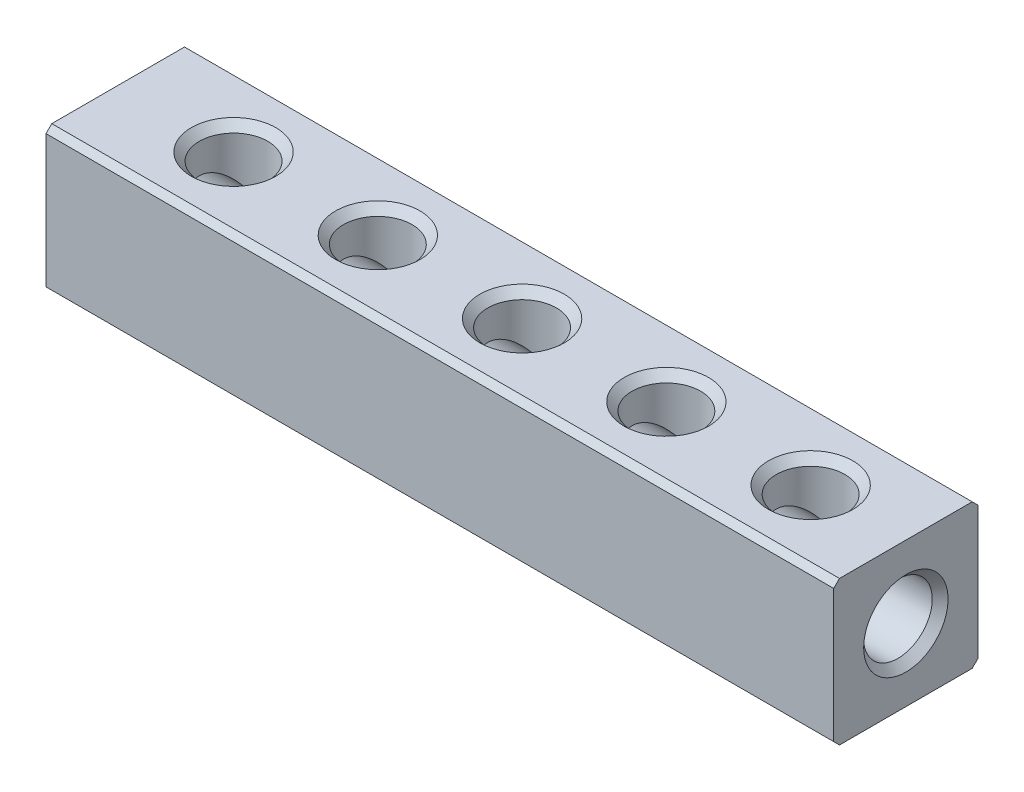
SolidWorks part; units mm, degrees
ref_plane "Front Plane" through (0, 0, 0) normal (0, 0, 1) x (1, 0, 0)
ref_plane "Top Plane" through (0, 0, 0) normal (0, 1, 0) x (1, 0, 0)
ref_plane "Right Plane" through (0, 0, 0) normal (1, 0, 0) x (0, 0, -1)
sketch "Sketch1" plane through (0, 0, 0) normal (0, 0, 1) x (1, 0, 0)
  line L1 (0, 0) -> (136.5, 0)
  line L2 (0, 0) -> (0, -25)
  line L3 (0, -25) -> (136.5, -25)
  line L4 (136.5, 0) -> (136.5, -25)
  dimension "D1" = 136.5
  dimension "D2" = 25
extrude "Boss-Extrude1" add sketch "Sketch1" along normal blind 25
sketch "Sketch4" plane through (0, 0, 0) normal (-1, 0, 0) x (0, 0, 1)
  line L0 (25, -25) -> (0, -25) construction
  line L1 (25, 0) -> (25, -25) construction
  circle A0 centre (12.5, -12.5) radius 6.55
  point P0 (12.5, -12.5)
  dimension "D1" = 13.1
  dimension "D2" = 12.5
  dimension "D3" = 12.5
sketch "Sketch5" plane through (0, -25, 0) normal (0, -1, 0) x (1, 0, 0)
  line L0 (0, 0) -> (136.5, 0) construction
  line L1 (0, 25) -> (0, 0) construction
  circle A0 centre (68.25, 12.5) radius 6.55
  dimension "D1" = 13.1
  dimension "D2" = 12.5
  dimension "D3" = 68.25
sketch "Sketch6" plane through (0, 0, 0) normal (0, 1, 0) x (1, 0, 0)
  line L0 (0, -25) -> (0, 0) construction
  line L1 (136.5, 0) -> (0, 0) construction
  circle A0 centre (20, -12.5) radius 6.55
  dimension "D1" = 13.1
  dimension "D2" = 20
  dimension "D3" = 12.5
hole_wizard "1/4-18 NPSM Tapped Hole2" positions "Sketch9" profile "Sketch10" tap size "1/4-18 NPSM" standard "ANSI Inch" end condition through all
sketch "Sketch9" plane through (0, 0, 0) normal (-1, 0, 0) x (0, 0, 1)
  point P0 (12.5, -12.5)
sketch "Sketch10" plane through (0, -12.5, 12.5) normal (0, 1, 0) x (0, 0, 1)
  line L0 (0, 0) -> (0, 136.5)
  line L1 (0, 136.5) -> (7.3152, 136.5)
  line L2 (5.9436, 135.1284) -> (5.9436, 1.3716)
  line L3 (5.9436, 1.3716) -> (7.3152, 0)
  line L5 (7.3152, 0) -> (0, 0)
  line L6 (-5.9436, 1.3716) -> (-7.3152, 0) construction
  line L7 (7.3152, 136.5) -> (5.9436, 135.1284)
  line L8 (-7.3152, 136.5) -> (-5.9436, 135.1284) construction
  line L11 (0, -6.35) -> (0, 107.95) construction
  dimension "Thru Tap Drill Dia." = 11.8872
  dimension "Thru Tap Drill Depth" = 136.5
  dimension "Near C'Sink Dia." = 14.6304
  dimension "Near C'Sink Angle" = 90
  dimension "Far C'Sink Dia." = 14.6304
  dimension "Far C'Sink Angle" = 90
cosmetic thread "Hole Thread2" parameters "D2"=13.3604
hole_wizard "1/4-18 NPSM Tapped Hole3" positions "Sketch22" profile "Sketch23" tap size "1/4-18 NPSM" standard "ANSI Inch"
sketch "Sketch22" plane through (0, -25, 0) normal (0, -1, 0) x (-1, 0, 0)
  point P0 (-68.25, -12.5)
sketch "Sketch23" plane through (68.25, -25, 12.5) normal (1, 0, 0) x (0, 0, -1)
  line L0 (0, 0) -> (0, 16.0703)
  line L1 (0, 16.0703) -> (5.9436, 12.499)
  line L2 (5.9436, 12.499) -> (5.9436, 1.3716)
  line L3 (5.9436, 1.3716) -> (7.3152, 0)
  line L5 (7.3152, 0) -> (0, 0)
  line L6 (-5.9436, 1.3716) -> (-7.3152, 0) construction
  line L10 (0, 16.0703) -> (-5.9436, 12.499) construction
  line L11 (0, -6.35) -> (0, 107.95) construction
  dimension "Tap Drill Dia." = 11.8872
  dimension "Tap Drill Depth" = 12.499
  dimension "Near C'Sink Dia." = 14.6304
  dimension "Near C'Sink Angle" = 90
  dimension "Drill Angle" = 118
cosmetic thread "Hole Thread3" parameters "D1"=26.72, "D2"=13.3604
hole_wizard "1/4-18 NPSM Tapped Hole4" positions "Sketch26" profile "Sketch27" tap size "1/4-18 NPSM" standard "ANSI Inch"
sketch "Sketch26" plane through (0, 0, 0) normal (0, 1, 0) x (1, 0, 0)
  point P0 (20, -12.5)
sketch "Sketch27" plane through (20, 0, 12.5) normal (1, 0, 0) x (0, 0, 1)
  line L0 (0, 0) -> (0, 16.0703)
  line L1 (0, 16.0703) -> (5.9436, 12.499)
  line L2 (5.9436, 12.499) -> (5.9436, 1.3716)
  line L3 (5.9436, 1.3716) -> (7.3152, 0)
  line L5 (7.3152, 0) -> (0, 0)
  line L6 (-5.9436, 1.3716) -> (-7.3152, 0) construction
  line L10 (0, 16.0703) -> (-5.9436, 12.499) construction
  line L11 (0, -6.35) -> (0, 107.95) construction
  dimension "Tap Drill Dia." = 11.8872
  dimension "Tap Drill Depth" = 12.499
  dimension "Near C'Sink Dia." = 14.6304
  dimension "Near C'Sink Angle" = 90
  dimension "Drill Angle" = 118
cosmetic thread "Hole Thread4" parameters "D1"=26.72, "D2"=13.3604
pattern_linear "LPattern2" count 5 spacing 25 along (1, 0, 0) of "1/4-18 NPSM Tapped Hole4"
cosmetic thread "Hole Thread9" parameters "D1"=26.72, "D2"=13.3604
cosmetic thread "Hole Thread10" parameters "D1"=26.72, "D2"=13.3604
cosmetic thread "Hole Thread11" parameters "D1"=26.72, "D2"=13.3604
cosmetic thread "Hole Thread12" parameters "D1"=26.72, "D2"=13.3604
chamfer "Chamfer1" distance 1 angle 45 4 edges at (68.25, 0, 0) (68.25, -25, 0) (68.25, -25, 25) (68.25, 0, 25)
